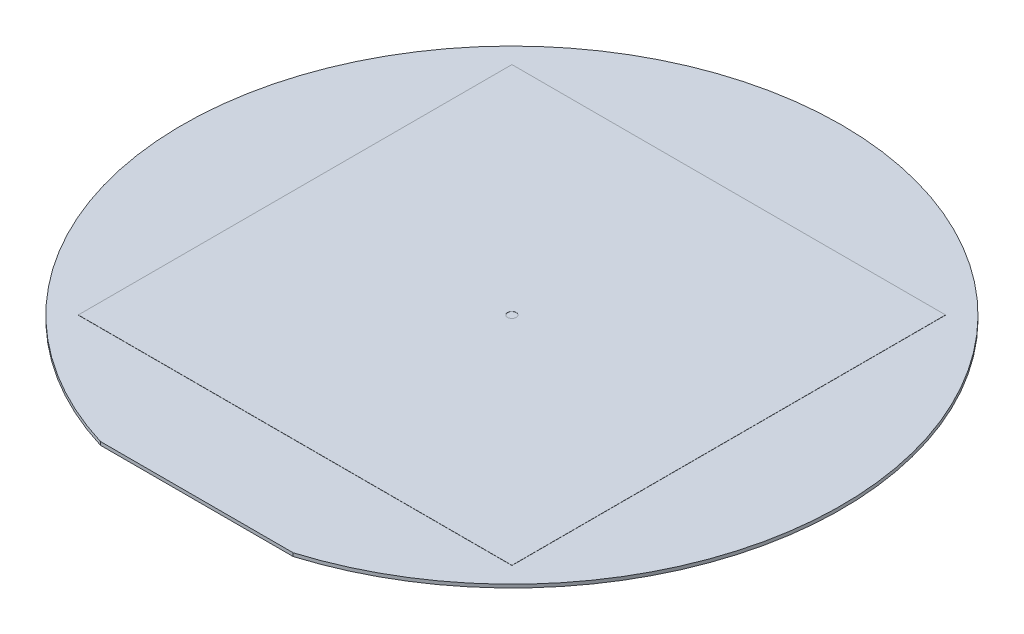
SolidWorks part; units mm, degrees
ref_plane "Front Plane" through (0, 0, 0) normal (0, 0, 1) x (1, 0, 0)
ref_plane "Top Plane" through (0, 0, 0) normal (0, 1, 0) x (1, 0, 0)
ref_plane "Right Plane" through (0, 0, 0) normal (1, 0, 0) x (0, 0, -1)
sketch "Sketch1" plane through (0, 0, 0) normal (0, 1, 0) x (1, 0, 0)
  line L1 (-25, 25) -> (25, 25)
  line L2 (-25, 25) -> (-25, -25)
  line L3 (-25, -25) -> (25, -25)
  line L4 (25, 25) -> (25, -25)
  line L5 (-25, 25) -> (25, -25) construction
  line L6 (-25, -25) -> (25, 25) construction
  circle A0 centre (0, 0) radius 0.5
  point P0 (0, 0)
  dimension "D2" = 1
  dimension "D1" = 50
extrude "Boss-Extrude1" add sketch "Sketch1" along normal blind 0.4
sketch "Sketch2" plane through (0, 0.4, 0) normal (0, 1, 0) x (1, 0, 0)
  line L0 (0, 25) -> (0, -25) construction
  line L1 (25, 25) -> (-25, 25) construction
  line L2 (-25, -25) -> (25, -25) construction
  line L3 (-25, 0) -> (25, 0) construction
  line L4 (-25, 25) -> (-25, -25) construction
  line L5 (25, -25) -> (25, 25) construction
sketch "Sketch3" plane through (0, 0, 0) normal (0, 1, 0) x (1, 0, 0)
  line L0 (-11.11, -36.3396) -> (11.11, -36.3396)
  circle A0 centre (0, 0) radius 38
  point P5 (0, -36.3396)
  dimension "D1" = 76
  dimension "D2" = 22.22
extrude "Boss-Extrude2" add sketch "Sketch3" along normal blind 0.381 contours L0 A0
